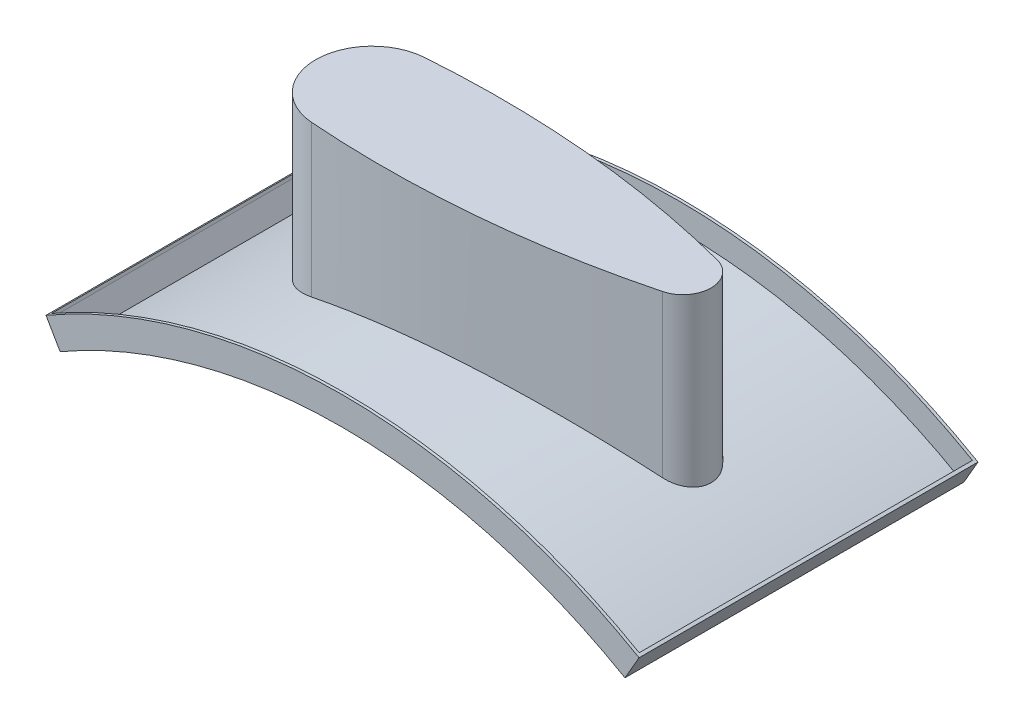
SolidWorks part; units mm, degrees
ref_plane "Front Plane" through (0, 0, 0) normal (0, 0, 1) x (1, 0, 0)
ref_plane "Top Plane" through (0, 0, 0) normal (0, 1, 0) x (1, 0, 0)
ref_plane "Right Plane" through (0, 0, 0) normal (1, 0, 0) x (0, 0, -1)
sketch "Sketch1" plane through (0, 0, 0) normal (0, 0, 1) x (1, 0, 0)
  line L0 (0, 0) -> (0, 110003.2118) construction
  line L1 (0, 0) -> (-110003.2118, 0) construction
  line L3 (-105, 181.8653) -> (-100, 173.2051)
  line L4 (105, 181.8653) -> (100, 173.2051)
  arc A1 (100, 173.2051) -> (-100, 173.2051) centre (0, 0) ccw
  arc A2 (105, 181.8653) -> (-105, 181.8653) centre (0, 0) ccw
  dimension "D1" = 10
  dimension "D2" = 200
extrude "Boss-Extrude1" add sketch "Sketch1" along normal blind 120
ref_plane "Plane1" through (0, 0, 119) normal (0, 0, 1) x (1, 0, 0)
sketch "Sketch2" plane through (0, 0, 119) normal (0, 0, 1) x (1, 0, 0)
  line L0 (-103.6328, 181.4972) -> (-99.6327, 174.569)
  line L1 (99.6327, 174.569) -> (103.6328, 181.4972)
  line L2 (-105, 181.8653) -> (-100, 173.2051)
  line L3 (100, 173.2051) -> (105, 181.8653)
  line L6 (-105, 184.5814) -> (-103.6328, 181.4972)
  line L7 (-105, 184.5814) -> (38.6122, 274.5886)
  line L8 (103.6328, 181.4972) -> (105, 184.5814)
  line L9 (105, 184.5814) -> (38.6122, 274.5886)
  line L12 (-105, 181.8653) -> (-100, 173.2051) construction
  line L13 (100, 173.2051) -> (105, 181.8653) construction
  arc A1 (99.6327, 174.569) -> (-99.6327, 174.569) centre (0, 0) ccw
  arc A2 (100, 173.2051) -> (-100, 173.2051) centre (0, 0) ccw
  arc A3 (105, 181.8653) -> (-105, 181.8653) centre (0, 0) ccw
  arc A5 (105, 181.8653) -> (104.0401, 182.4161) centre (0, 0) ccw
  arc A7 (105, 181.8653) -> (-105, 181.8653) centre (0, 0) ccw construction
  arc A8 (103.6328, 181.4972) -> (-103.6328, 181.4972) centre (0, 0) ccw construction
  arc A9 (100, 173.2051) -> (-100, 173.2051) centre (0, 0) ccw construction
  dimension "D1" = 0
  dimension "D2" = 1
extrude "Cut-Extrude1" cut sketch "Sketch2" against normal blind 118 contours A1 L1 L8 L9 L7 L6 L0
sketch "Sketch3" plane through (0, 0, 0) normal (0, 1, 0) x (1, 0, 0)
  line L1 (-49.5154, -60) -> (60.4846, -60) construction
  arc A0 (-51.003, -40.0554) -> (-51.003, -79.9446) centre (-49.5154, -60) ccw
  arc A1 (62.998, -69.679) -> (62.998, -50.321) centre (60.4846, -60) ccw
  arc A2 (-51.003, -40.0554) -> (62.998, -50.321) centre (-24.97, -389.0859) cw
  arc A3 (-51.003, -79.9446) -> (62.998, -69.679) centre (-24.97, 269.0859) ccw
  dimension "D1" = 40
  dimension "D2" = 20
  dimension "D3" = 350
  dimension "D4" = 110
  dimension "D5" = 0
  dimension "D6" = 60
extrude "Boss-Extrude2" add sketch "Sketch3" along normal blind 248
sketch "Sketch4" plane through (0, 0, 0) normal (0, 0, 1) x (1, 0, 0)
  line L0 (-69.5154, 187.5303) -> (-69.5154, 0) construction
  line L1 (70.4846, 0) -> (70.4846, 187.1682) construction
  line L2 (70.4846, 187.1682) -> (163.1468, -79.7502)
  line L3 (163.1468, -79.7502) -> (-229.1311, -106.9917)
  line L4 (-229.1311, -106.9917) -> (-69.5154, 187.5303)
  arc A0 (-69.5154, 187.5303) -> (70.4846, 187.1682) centre (0, 0) cw
  arc A1 (100, 173.2051) -> (-100, 173.2051) centre (0, 0) ccw construction
extrude "Cut-Extrude2" cut sketch "Sketch4" along normal blind 269
